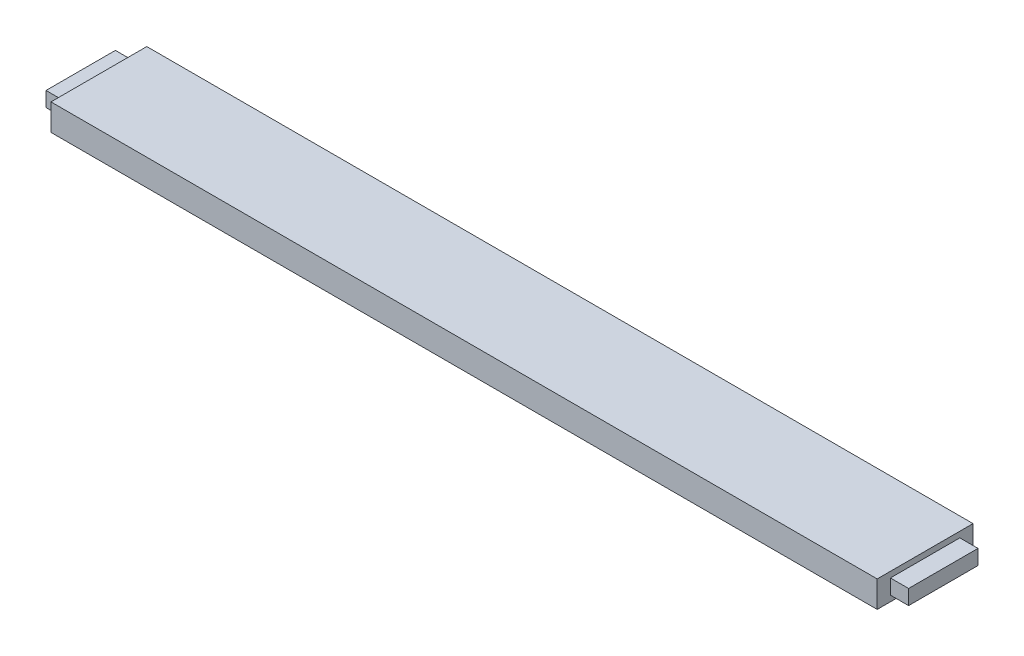
SolidWorks part; units mm, degrees
ref_plane "Спереди" through (0, 0, 0) normal (0, 0, 1) x (1, 0, 0)
ref_plane "Сверху" through (0, 0, 0) normal (0, 1, 0) x (1, 0, 0)
ref_plane "Справа" through (0, 0, 0) normal (1, 0, 0) x (0, 0, -1)
sketch "Эскиз1" plane through (0, 0, 0) normal (0, 1, 0) x (1, 0, 0)
  line L1 (-125, -14.4985) -> (125, -14.4985)
  line L2 (-125, -14.4985) -> (-125, 14.4985)
  line L3 (-125, 14.4985) -> (125, 14.4985)
  line L4 (125, -14.4985) -> (125, 14.4985)
  line L5 (-125, -14.4985) -> (125, 14.4985) construction
  line L6 (-125, 14.4985) -> (125, -14.4985) construction
  point P0 (0, 0)
  dimension "D1" = 28.997
  dimension "D2" = 250
extrude "Бобышка-Вытянуть1" add sketch "Эскиз1" along normal blind 8
sketch "Эскиз2" plane through (125, 0, 0) normal (1, 0, 0) x (0, 0, -1)
  line L0 (14.4985, 8) -> (-14.4985, 0) construction
  line L2 (-10.5009, 6.2506) -> (10.5009, 6.2506)
  line L3 (-10.5009, 6.2506) -> (-10.5009, 1.7494)
  line L4 (-10.5009, 1.7494) -> (10.5009, 1.7494)
  line L5 (10.5009, 6.2506) -> (10.5009, 1.7494)
  line L6 (-10.5009, 6.2506) -> (10.5009, 1.7494) construction
  line L7 (-10.5009, 1.7494) -> (10.5009, 6.2506) construction
  point P4 (0, 4)
extrude "Бобышка-Вытянуть2" add sketch "Эскиз2" along normal blind 5.5
sketch "Эскиз3" plane through (-125, 0, 0) normal (-1, 0, 0) x (0, 0, 1)
  line L0 (-14.4985, 0) -> (14.4985, 8) construction
  line L2 (10.4992, 1.752) -> (-10.4992, 1.752)
  line L3 (10.4992, 1.752) -> (10.4992, 6.248)
  line L4 (10.4992, 6.248) -> (-10.4992, 6.248)
  line L5 (-10.4992, 1.752) -> (-10.4992, 6.248)
  line L6 (10.4992, 1.752) -> (-10.4992, 6.248) construction
  line L7 (10.4992, 6.248) -> (-10.4992, 1.752) construction
  point P4 (0, 4)
extrude "Бобышка-Вытянуть3" add sketch "Эскиз3" along normal blind 5.5
